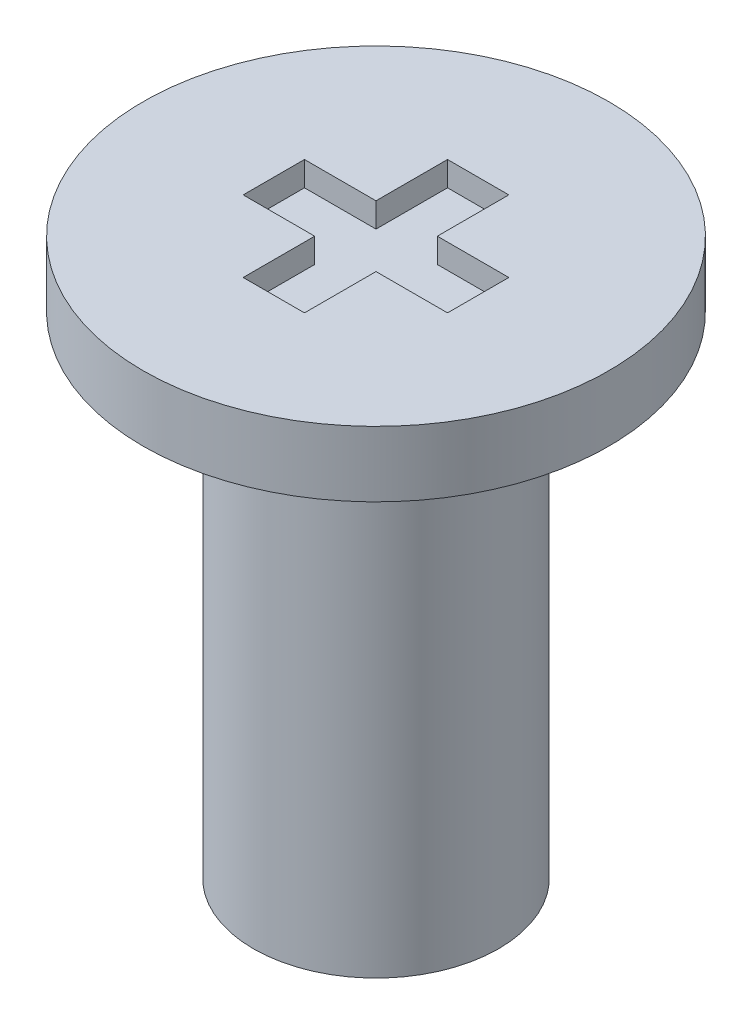
SolidWorks part; units mm, degrees
material "S45C"
ref_plane "正面" through (0, 0, 0) normal (0, 0, 1) x (1, 0, 0)
ref_plane "平面" through (0, 0, 0) normal (0, 1, 0) x (1, 0, 0)
ref_plane "右側面" through (0, 0, 0) normal (1, 0, 0) x (0, 0, -1)
sketch "ｽｹｯﾁ1" plane through (0, 0, 0) normal (0, 0, 1) x (1, 0, 0)
  line L0 (0, 0) -> (2.85, 0)
  line L1 (2.85, 0) -> (2.85, -0.8)
  line L2 (2.85, -0.8) -> (1.5, -0.8)
  line L3 (1.5, -0.8) -> (1.5, -6.8)
  line L4 (1.5, -6.8) -> (0, -6.8)
  line L5 (0, -6.8) -> (0, 0)
  dimension "D1" = 2.85
  dimension "D2" = 0.8
  dimension "D3" = 1.5
  dimension "D4" = 6
revolve "回転1" add sketch "ｽｹｯﾁ1" angle 360 about L5
sketch "ｽｹｯﾁ2" plane through (0, 0, 0) normal (0, 1, 0) x (1, 0, 0)
  line L1 (-0.375, 0) -> (0.375, 0)
  line L2 (-0.375, 0) -> (-0.375, 1.25)
  line L3 (-0.375, 1.25) -> (0.375, 1.25)
  line L4 (0.375, 0) -> (0.375, 1.25)
  line L5 (-0.375, 0) -> (0.375, 1.25) construction
  line L6 (-0.375, 1.25) -> (0.375, 0) construction
  point P4 (0, 0.625)
  dimension "D1" = 0
  dimension "D2" = 0.75
  dimension "D3" = 1.25
  dimension "D4" = 0
extrude "ｶｯﾄ - 押し出し1" cut sketch "ｽｹｯﾁ2" against normal blind 0.3
pattern_circular "円形ﾊﾟﾀｰﾝ1" count 4 over 360 about axis through (0, 0, 0) along (0, 1, 0) of "ｶｯﾄ - 押し出し1"
